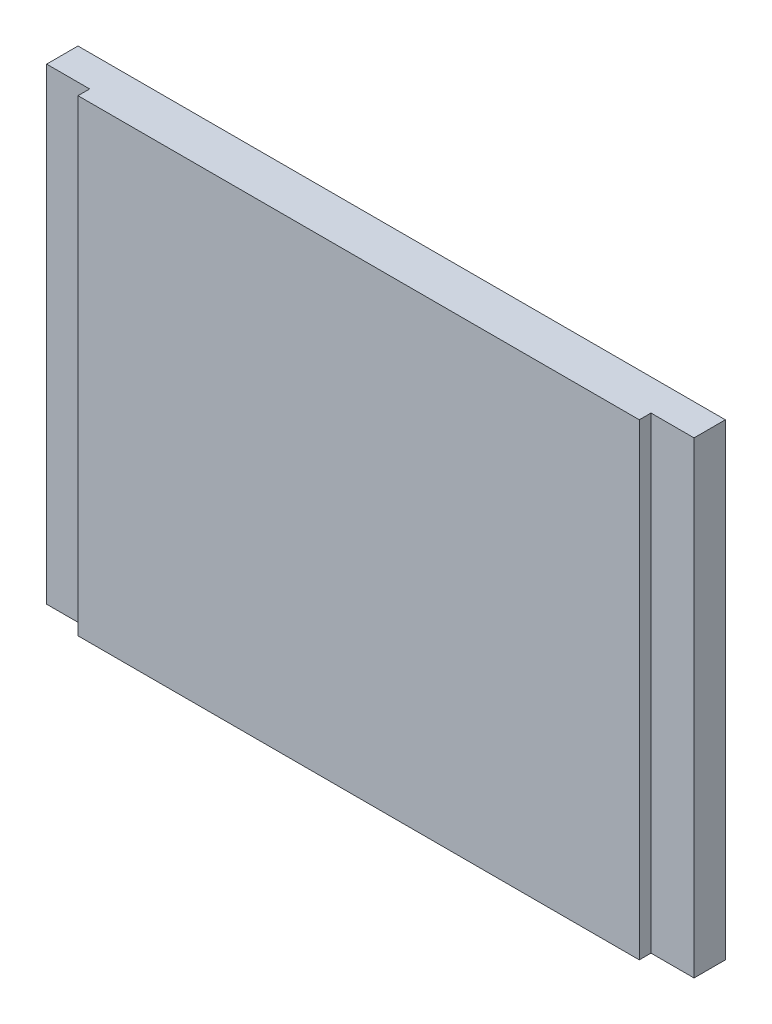
SolidWorks part; units mm, degrees
material "Acrylic (Medium-high impact)"
ref_plane "Front Plane" through (0, 0, 0) normal (0, 0, 1) x (1, 0, 0)
ref_plane "Top Plane" through (0, 0, 0) normal (0, 1, 0) x (1, 0, 0)
ref_plane "Right Plane" through (0, 0, 0) normal (1, 0, 0) x (0, 0, -1)
sketch "Sketch1" plane through (0, 0, 0) normal (0, 0, 1) x (1, 0, 0)
  line L1 (0, 0) -> (87.884, 0)
  line L2 (0, 0) -> (0, 63.5)
  line L3 (0, 63.5) -> (87.884, 63.5)
  line L4 (87.884, 0) -> (87.884, 63.5)
  dimension "D1" = 63.5
  dimension "D2" = 87.884
extrude "Boss-Extrude1" add sketch "Sketch1" along normal blind 5.842 contours L2 L3 L4 L1
sketch "Sketch2" plane through (0, 0, 5.842) normal (0, 0, 1) x (1, 0, 0)
  line L0 (0, 63.5) -> (87.884, 63.5) construction
  line L1 (0, 0) -> (5.842, 0)
  line L2 (0, 0) -> (0, 63.5)
  line L3 (0, 63.5) -> (5.842, 63.5)
  line L4 (5.842, 0) -> (5.842, 63.5)
  line L5 (0, 0) -> (87.884, 0) construction
  line L6 (87.884, 63.5) -> (82.042, 63.5)
  line L7 (87.884, 63.5) -> (87.884, 0)
  line L8 (87.884, 0) -> (82.042, 0)
  line L9 (82.042, 63.5) -> (82.042, 0)
  dimension "D1" = 76.2
extrude "Cut-Extrude1" cut sketch "Sketch2" against normal blind 1.5875
sketch "Sketch3" plane through (0, 0, 0) normal (0, 0, -1) x (-1, 0, 0)
  line L0 (-68.2434, 19.05) -> (-19.6405, 19.05) construction
  line L1 (-43.942, 0) -> (-43.942, 19.05) construction
  line L2 (0, 0) -> (-87.884, 0) construction
  circle A0 centre (-68.2434, 19.05) radius 5.5563
  circle A1 centre (-19.6405, 19.05) radius 5.5562
  dimension "D3" = 11.1125
  dimension "D1" = 19.05
  dimension "D2" = 48.6029
extrude "Cut-Extrude2" [suppressed] cut sketch "Sketch3" against normal blind 7.62
